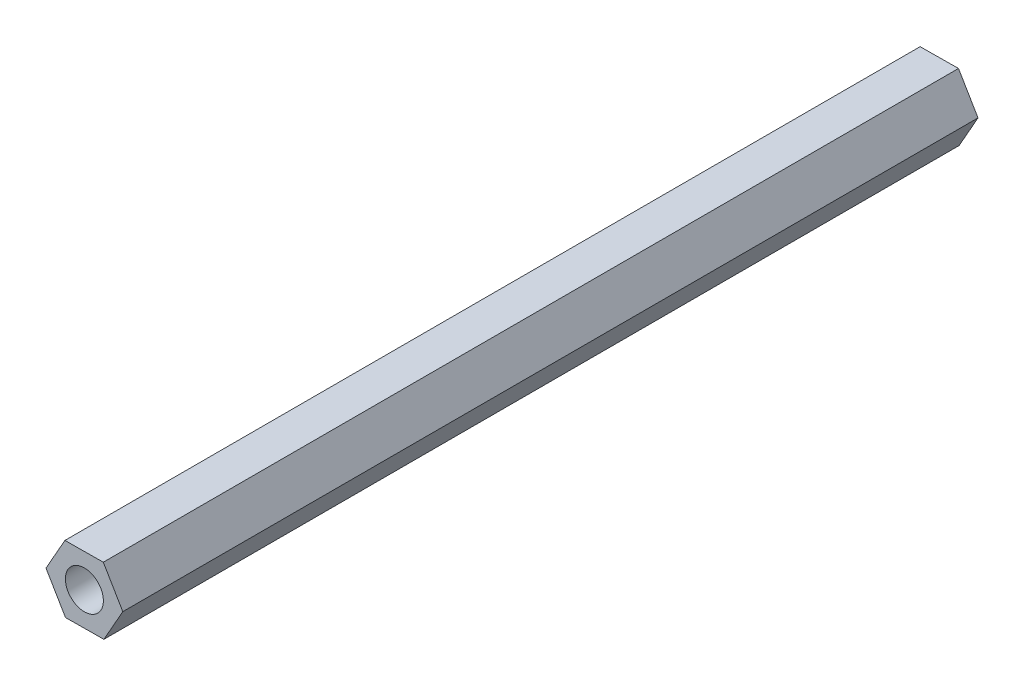
SolidWorks part; units mm, degrees
ref_plane "前视基准面" through (0, 0, 0) normal (0, 0, 1) x (1, 0, 0)
ref_plane "上视基准面" through (0, 0, 0) normal (0, 1, 0) x (1, 0, 0)
ref_plane "右视基准面" through (0, 0, 0) normal (1, 0, 0) x (0, 0, -1)
sketch "草图1" plane through (0, 0, 0) normal (0, 0, 1) x (1, 0, 0)
  line L1 (2.0515, -3.4821) -> (4.0413, 0.0356)
  line L2 (4.0413, 0.0356) -> (1.9898, 3.5177)
  line L3 (1.9898, 3.5177) -> (-2.0515, 3.4821)
  line L4 (-2.0515, 3.4821) -> (-4.0413, -0.0356)
  line L5 (-4.0413, -0.0356) -> (-1.9898, -3.5177)
  line L6 (-1.9898, -3.5177) -> (2.0515, -3.4821)
  circle A0 centre (0, 0) radius 3.5 construction
  circle A1 centre (0, 0) radius 2
extrude "凸台-拉伸1" add sketch "草图1" along normal blind 90
